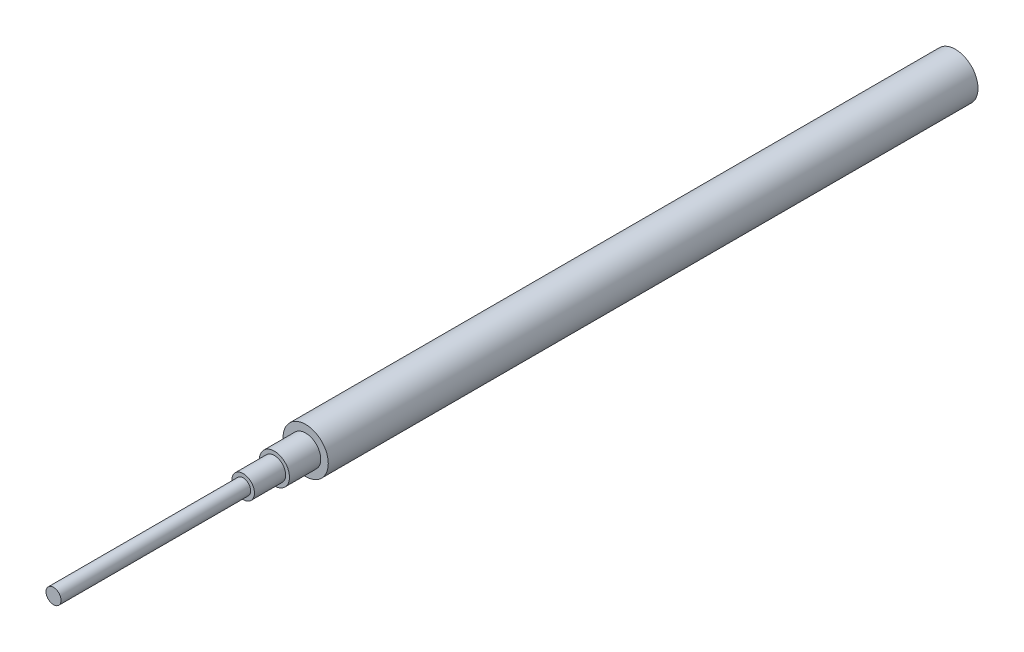
SolidWorks part; units mm, degrees
material "Plain Carbon Steel"
ref_plane "Front Plane" through (0, 0, 0) normal (0, 0, 1) x (1, 0, 0)
ref_plane "Top Plane" through (0, 0, 0) normal (0, 1, 0) x (1, 0, 0)
ref_plane "Right Plane" through (0, 0, 0) normal (1, 0, 0) x (0, 0, -1)
sketch "Sketch1" plane through (0, 0, 0) normal (0, 0, 1) x (1, 0, 0)
  circle A0 centre (0, 0) radius 4.7625
  dimension "D1" = 9.525
extrude "Boss-Extrude1" add sketch "Sketch1" along normal blind 136.88
sketch "Sketch2" plane through (0, 0, 0) normal (0, 0, 1) x (1, 0, 0)
  circle A0 centre (0, 0) radius 3.175
  dimension "D1" = 6.35
extrude "Boss-Extrude2" add sketch "Sketch2" along normal blind 143.47
sketch "Sketch3" plane through (0, 0, 0) normal (0, 0, 1) x (1, 0, 0)
  circle A0 centre (0, 0) radius 2.3812
  dimension "D1" = 4.7625
extrude "Boss-Extrude3" add sketch "Sketch3" along normal blind 150.05
sketch "Sketch4" plane through (0, 0, 0) normal (0, 0, 1) x (1, 0, 0)
  circle A0 centre (0, 0) radius 1.5875
  dimension "D1" = 3.175
extrude "Boss-Extrude4" add sketch "Sketch4" along normal blind 190
